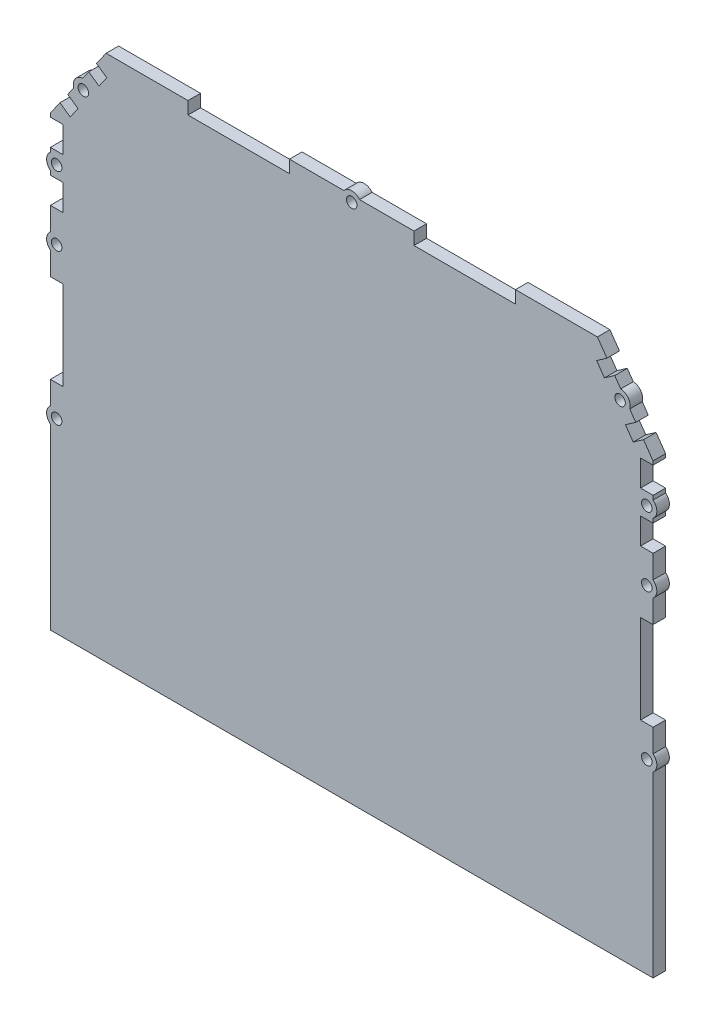
SolidWorks part; units mm, degrees
ref_plane "Front Plane" through (0, 0, 0) normal (0, 0, 1) x (1, 0, 0)
ref_plane "Top Plane" through (0, 0, 0) normal (0, 1, 0) x (1, 0, 0)
ref_plane "Right Plane" through (0, 0, 0) normal (1, 0, 0) x (0, 0, -1)
sketch "Sketch1" plane through (0, 0, 0) normal (0, 0, 1) x (1, 0, 0)
  line L0 (-120, 40) -> (-42.5, 40)
  line L1 (120, 105) -> (-120, 105)
  line L2 (120, 105) -> (120, 40)
  line L3 (120, -105) -> (-120, -105)
  line L4 (-120, 105) -> (-120, 40)
  line L5 (120, 105) -> (-120, -105) construction
  line L6 (120, -105) -> (-120, 105) construction
  line L7 (-42.5, 40) -> (-42.5, -40)
  line L8 (-42.5, -40) -> (-120, -40)
  line L9 (120, 40) -> (42.5, 40)
  line L10 (42.5, 40) -> (42.5, -40)
  line L11 (42.5, -40) -> (120, -40)
  line L12 (-120, -40) -> (-120, -105)
  line L13 (120, -40) -> (120, -105)
  point P0 (0, 0)
  point P12 (-120, 0)
  point P15 (120, 0)
  point P16 (-42.5, 0)
  point P18 (42.5, 0)
  dimension "D1" = 240
  dimension "D2" = 210
  dimension "D3" = 77.5
  dimension "D4" = 77.5
  dimension "D5" = 80
extrude "Boss-Extrude1" add sketch "Sketch1" along normal blind 5
sketch "Sketch2" plane through (0, 0, 5) normal (0, 0, 1) x (1, 0, 0)
  line L0 (-120, -105) -> (120, -105) construction
  line L1 (40, -55.718) -> (-40, -55.718)
  line L2 (-40, -55.718) -> (-80, -125)
  line L3 (-80, -125) -> (-40, -194.282)
  line L4 (-40, -194.282) -> (40, -194.282)
  line L5 (40, -194.282) -> (80, -125)
  line L6 (80, -125) -> (40, -55.718)
  circle A0 centre (0, -125) radius 69.282 construction
  dimension "D1" = 160
  dimension "D2" = 20
extrude "Cut-Extrude1" cut sketch "Sketch2" against normal blind 5
sketch "Sketch5" plane through (0, 0, 5) normal (0, 0, 1) x (1, 0, 0)
  line L0 (-97.5, 95) -> (-101, 90) construction
  line L1 (-97.8239, 105) -> (-120, 73.3199)
  line L2 (120, 105) -> (-120, 105) construction
  line L3 (-120, 105) -> (-120, 40) construction
  line L4 (-97.8239, 105) -> (-120, 105)
  line L5 (-120, 105) -> (-120, 73.3199)
  line L6 (0, 105) -> (0, 62.0384) construction
  line L7 (97.8239, 105) -> (120, 105)
  line L8 (97.8239, 105) -> (120, 73.3199)
  line L9 (120, 105) -> (120, 73.3199)
  dimension "D1" = 6
extrude "Cut-Extrude4" cut sketch "Sketch5" against normal blind 5
sketch "Sketch7" plane through (0, 0, 0) normal (0, 0, -1) x (-1, 0, 0)
  line L0 (120, -40) -> (120, -105)
  line L1 (120, -40) -> (120, -105) construction
  line L2 (120, -105) -> (89.53, -105)
  line L5 (129.53, -122.5) -> (129.53, -40)
  line L6 (129.53, -40) -> (89.53, -40)
  line L7 (89.53, -40) -> (89.53, -64)
  line L8 (89.53, -105) -> (111.53, -122.5)
  line L9 (111.53, -122.5) -> (129.53, -122.5)
  line L10 (129.53, -122.5) -> (129.53, -40)
  line L11 (129.53, -40) -> (120, -40)
  line L13 (89.53, -105) -> (111.53, -122.5)
  line L14 (111.53, -122.5) -> (129.53, -122.5)
  line L40 (89.53, -94) -> (89.53, -105)
  arc A2 (89.53, -94) -> (89.53, -64) centre (89.53, -79) ccw
  dimension "D1" = 0
extrude "Boss-Extrude3" add sketch "Sketch7" against normal blind 5
mirror "Mirror2" about plane through (0, 0, 0) normal (1, 0, 0) of "Boss-Extrude3"
sketch "Sketch8" plane through (0, 0, 5) normal (0, 0, 1) x (1, 0, 0)
  line L0 (-108.912, 89.16) -> (-95.8237, 79.9982) construction
  line L1 (-113.2129, 83.0157) -> (-116.0802, 78.9196)
  line L14 (-120, 73.3199) -> (-97.8239, 105) construction
  line L15 (-100.5148, 92.4369) -> (-104.611, 95.3042)
  line L28 (-120, 56.66) -> (-98.9329, 56.66) construction
  line L29 (-120, 73.3199) -> (-120, 40) construction
  line L30 (0, 105) -> (0, 80.5082) construction
  line L31 (97.8239, 105) -> (-97.8239, 105) construction
  line L32 (-116.0802, 78.9196) -> (-111.9841, 76.0522)
  line L33 (-111.9841, 76.0522) -> (-109.1168, 80.1484)
  line L34 (-109.1168, 80.1484) -> (-113.2129, 83.0157)
  line L35 (-110.5504, 78.1003) -> (-114.6466, 80.9676) construction
  line L36 (-97.6475, 96.533) -> (-100.5148, 92.4369)
  line L37 (-101.7437, 99.4004) -> (-97.6475, 96.533)
  line L38 (-104.611, 95.3042) -> (-101.7437, 99.4004)
  line L39 (-120, 41.66) -> (-115, 41.66)
  line L40 (-115, 41.66) -> (-115, 51.66)
  line L41 (-115, 51.66) -> (-120, 51.66)
  line L42 (-120, 51.66) -> (-120, 41.66)
  line L43 (-115, 61.66) -> (-120, 61.66)
  line L44 (-115, 71.66) -> (-115, 61.66)
  line L45 (-120, 71.66) -> (-115, 71.66)
  line L46 (-120, 61.66) -> (-120, 71.66)
  line L47 (110.5504, 78.1003) -> (114.6466, 80.9676) construction
  line L48 (-65, 105) -> (-25, 105)
  line L49 (-65, 105) -> (-65, 100)
  line L50 (-65, 100) -> (-25, 100)
  line L51 (-25, 105) -> (-25, 100)
  line L52 (120, 56.66) -> (98.9329, 56.66) construction
  line L53 (108.912, 89.16) -> (95.8237, 79.9982) construction
  line L54 (25, 105) -> (25, 100)
  line L55 (65, 100) -> (25, 100)
  line L56 (65, 105) -> (65, 100)
  line L57 (65, 105) -> (25, 105)
  line L58 (120, 61.66) -> (120, 71.66)
  line L59 (120, 71.66) -> (115, 71.66)
  line L60 (115, 71.66) -> (115, 61.66)
  line L61 (115, 61.66) -> (120, 61.66)
  line L62 (120, 51.66) -> (120, 41.66)
  line L63 (115, 51.66) -> (120, 51.66)
  line L64 (115, 41.66) -> (115, 51.66)
  line L65 (120, 41.66) -> (115, 41.66)
  line L66 (104.611, 95.3042) -> (101.7437, 99.4004)
  line L67 (101.7437, 99.4004) -> (97.6475, 96.533)
  line L68 (97.6475, 96.533) -> (100.5148, 92.4369)
  line L69 (109.1168, 80.1484) -> (113.2129, 83.0157)
  line L70 (111.9841, 76.0522) -> (109.1168, 80.1484)
  line L71 (116.0802, 78.9196) -> (111.9841, 76.0522)
  line L72 (100.5148, 92.4369) -> (104.611, 95.3042)
  line L73 (113.2129, 83.0157) -> (116.0802, 78.9196)
  line L75 (97.8239, 105) -> (120, 73.3199) construction
  line L76 (120, 40) -> (120, 73.3199) construction
  circle A0 centre (0, 102.5) radius 2.1
  circle A2 centre (106.8639, 87.7263) radius 2.1
  circle A3 centre (117.5, 56.66) radius 2.1
  circle A4 centre (-117.5, 56.66) radius 2.1
  circle A5 centre (-106.8639, 87.7263) radius 2.1
  dimension "D10" = 4.2
  dimension "D11" = 2.5
  dimension "D12" = 4.2
  dimension "D13" = 2.5
  dimension "D14" = 4.2
  dimension "D15" = 2.5
  dimension "D3" = 10
  dimension "D1" = 5
  dimension "D2" = 5
  dimension "D4" = 10
  dimension "D5" = 5
  dimension "D6" = 5
  dimension "D7" = 40
  dimension "D8" = 5
  dimension "D9" = 25
extrude "Cut-Extrude5" cut sketch "Sketch8" against normal blind 10
sketch "Sketch9" plane through (0, 0, 5) normal (0, 0, 1) x (1, 0, 0)
  line L0 (-3.1225, 105) -> (3.1225, 105)
  line L1 (25, 105) -> (-25, 105) construction
  line L2 (107.1213, 91.718) -> (110.7026, 86.6019)
  line L3 (104.611, 95.3042) -> (113.2129, 83.0157) construction
  line L4 (120, 59.7825) -> (120, 53.5375)
  line L5 (120, 51.66) -> (120, 61.66) construction
  line L6 (0, 102.5) -> (0, 84.4431) construction
  line L7 (-120, 59.7825) -> (-120, 53.5375)
  line L8 (-107.1213, 91.718) -> (-110.7026, 86.6019)
  arc A0 (3.1225, 105) -> (-3.1225, 105) centre (0, 102.5) ccw
  arc A1 (110.7026, 86.6019) -> (107.1213, 91.718) centre (106.8639, 87.7263) ccw
  arc A2 (120, 53.5375) -> (120, 59.7825) centre (117.5, 56.66) ccw
  arc A3 (-120, 53.5375) -> (-120, 59.7825) centre (-117.5, 56.66) cw
  arc A4 (-110.7026, 86.6019) -> (-107.1213, 91.718) centre (-106.8639, 87.7263) cw
  dimension "D1" = 8
  dimension "D2" = 8
  dimension "D3" = 8
extrude "Boss-Extrude4" add sketch "Sketch9" against normal blind 5
sketch "Sketch10" plane through (0, 0, 5) normal (0, 0, 1) x (1, 0, 0)
  line L0 (-120, 40) -> (-120, -40)
  line L1 (-68.453, -105) -> (68.453, -105)
  line L2 (120, -40) -> (120, 40)
  line L3 (68.453, -105) -> (89.53, -105) construction
  line L4 (-120, 40) -> (-42.5, 40)
  line L5 (-42.5, 40) -> (-42.5, -40)
  line L6 (-42.5, -40) -> (-120, -40)
  line L7 (-42.5, -40) -> (-129.53, -40) construction
  line L8 (-40, -55.718) -> (-68.453, -105)
  line L9 (-40, -55.718) -> (40, -55.718)
  line L10 (40, -55.718) -> (68.453, -105)
  line L11 (120, -40) -> (42.5, -40)
  line L12 (129.53, -40) -> (42.5, -40) construction
  line L13 (42.5, -40) -> (42.5, 40)
  line L14 (42.5, 40) -> (120, 40)
  point P9 (78.9915, -105)
extrude "Boss-Extrude5" add sketch "Sketch10" against normal blind 5
sketch "Sketch11" plane through (0, 0, 5) normal (0, 0, 1) x (1, 0, 0)
  line L0 (-120, -40) -> (-120, -105)
  line L1 (-120, -105) -> (120, -105)
  line L2 (120, -105) -> (120, -40)
  line L3 (120, -40) -> (129.53, -40)
  line L4 (129.53, -40) -> (129.53, -122.5)
  line L5 (129.53, -122.5) -> (-129.53, -122.5)
  line L6 (-129.53, -122.5) -> (-129.53, -40)
  line L7 (-129.53, -40) -> (-120, -40)
  line L8 (-89.53, -105) -> (89.53, -105) construction
extrude "Cut-Extrude6" cut sketch "Sketch11" against normal blind 5
sketch "Sketch12" plane through (0, 0, 5) normal (0, 0, 1) x (1, 0, 0)
  line L0 (-120, 41.66) -> (-120, -105) construction
  line L1 (-120, 16.66) -> (-115, 16.66)
  line L2 (-120, 16.66) -> (-120, -18.34)
  line L3 (-120, -18.34) -> (-115, -18.34)
  line L4 (-115, 16.66) -> (-115, -18.34)
  line L5 (-120, 41.66) -> (-115, 41.66) construction
  line L6 (0, 0) -> (0, -46.7623) construction
  line L7 (115, 16.66) -> (115, -18.34)
  line L8 (120, -18.34) -> (115, -18.34)
  line L9 (120, 16.66) -> (120, -18.34)
  line L10 (120, 16.66) -> (115, 16.66)
  circle A0 centre (-117.5, 29.16) radius 2.1
  circle A1 centre (-117.5, -30.84) radius 2.1
  circle A2 centre (117.5, -30.84) radius 2.1
  circle A3 centre (117.5, 29.16) radius 2.1
  dimension "D3" = 4.2
  dimension "D4" = 2.5
  dimension "D5" = 12.5
  dimension "D7" = 4.2
  dimension "D8" = 12.5
  dimension "D9" = 2.5
  dimension "D1" = 35
  dimension "D2" = 25
  dimension "D6" = 5
extrude "Cut-Extrude7" cut sketch "Sketch12" against normal blind 5
sketch "Sketch13" plane through (0, 0, 5) normal (0, 0, 1) x (1, 0, 0)
  line L0 (-120, 32.2825) -> (-120, 26.0375)
  line L1 (-120, 41.66) -> (-120, 16.66) construction
  line L2 (-120, -27.7175) -> (-120, -33.9625)
  line L3 (-120, -18.34) -> (-120, -105) construction
  line L4 (0, 0) -> (0, -42.8158) construction
  line L5 (120, -27.7175) -> (120, -33.9625)
  line L6 (120, 32.2825) -> (120, 26.0375)
  arc A0 (-120, 32.2825) -> (-120, 26.0375) centre (-117.5, 29.16) ccw
  arc A1 (-120, -27.7175) -> (-120, -33.9625) centre (-117.5, -30.84) ccw
  arc A2 (120, -27.7175) -> (120, -33.9625) centre (117.5, -30.84) cw
  arc A3 (120, 32.2825) -> (120, 26.0375) centre (117.5, 29.16) cw
  dimension "D1" = 8
  dimension "D2" = 8
extrude "Boss-Extrude6" add sketch "Sketch13" against normal blind 5
sketch "Sketch14" plane through (0, 0, 5) normal (0, 0, 1) x (1, 0, 0)
  line L0 (-104.7257, 95.1403) -> (-100.6295, 92.273)
  line L1 (-107.1213, 91.718) -> (-104.611, 95.3042) construction
  line L2 (-100.6295, 92.273) -> (-97.5328, 96.6969)
  line L3 (-97.5328, 96.6969) -> (-101.629, 99.5642)
  line L4 (-101.7437, 99.4004) -> (-97.8239, 105) construction
  line L5 (-104.611, 95.3042) -> (-100.5148, 92.4369) construction
  line L6 (-100.5148, 92.4369) -> (-97.6475, 96.533) construction
  line L7 (-110.1408, 90.0201) -> (-106.8639, 87.7263) construction
  line L8 (-112.0988, 75.8884) -> (-116.1949, 78.7557)
  line L9 (-109.0021, 80.3122) -> (-112.0988, 75.8884)
  line L10 (-113.0982, 83.1796) -> (-109.0021, 80.3122)
  line L11 (-120, 73.3199) -> (-120, 71.66) construction
  line L12 (-120, 71.86) -> (-115, 71.86)
  line L13 (-120, 71.86) -> (-120, 61.46)
  line L14 (-120, 61.46) -> (-115, 61.46)
  line L15 (-115, 71.86) -> (-115, 61.46)
  line L16 (-120, 61.66) -> (-115, 61.66) construction
  line L17 (-121.5, 56.66) -> (-117.5, 56.66) construction
  line L18 (-115, 41.46) -> (-115, 51.86)
  line L19 (-120, 51.86) -> (-115, 51.86)
  line L20 (-120, 41.46) -> (-120, 51.86)
  line L21 (-120, 41.46) -> (-115, 41.46)
  line L22 (-120, -18.34) -> (-120, -27.7175) construction
  line L23 (-115, 16.86) -> (-120, 16.86)
  line L24 (-115, 16.86) -> (-115, -18.54)
  line L25 (-115, -18.54) -> (-120, -18.54)
  line L26 (-120, 16.86) -> (-120, -18.54)
  line L27 (-120, -18.34) -> (-115, -18.34) construction
  line L28 (-65, 105) -> (-97.8239, 105) construction
  line L29 (-65.2, 105) -> (-24.8, 105)
  line L30 (-65.2, 105) -> (-65.2, 100)
  line L31 (-65.2, 100) -> (-24.8, 100)
  line L32 (-24.8, 105) -> (-24.8, 100)
  line L33 (-65, 105) -> (-65, 100) construction
  line L34 (0, 102.5) -> (0, 85.714) construction
  line L35 (24.8, 105) -> (24.8, 100)
  line L36 (65.2, 100) -> (24.8, 100)
  line L37 (65.2, 105) -> (65.2, 100)
  line L38 (65.2, 105) -> (24.8, 105)
  line L39 (121.5, 56.66) -> (117.5, 56.66) construction
  line L40 (110.1408, 90.0201) -> (106.8639, 87.7263) construction
  line L41 (120, 16.86) -> (120, -18.54)
  line L42 (115, -18.54) -> (120, -18.54)
  line L43 (115, 16.86) -> (115, -18.54)
  line L44 (115, 16.86) -> (120, 16.86)
  line L45 (120, 41.46) -> (115, 41.46)
  line L46 (120, 41.46) -> (120, 51.86)
  line L47 (120, 51.86) -> (115, 51.86)
  line L48 (115, 41.46) -> (115, 51.86)
  line L49 (115, 71.86) -> (115, 61.46)
  line L50 (120, 61.46) -> (115, 61.46)
  line L51 (120, 71.86) -> (120, 61.46)
  line L52 (120, 71.86) -> (115, 71.86)
  line L53 (113.0982, 83.1796) -> (109.0021, 80.3122)
  line L54 (109.0021, 80.3122) -> (112.0988, 75.8884)
  line L55 (112.0988, 75.8884) -> (116.1949, 78.7557)
  line L56 (97.5328, 96.6969) -> (101.629, 99.5642)
  line L57 (100.6295, 92.273) -> (97.5328, 96.6969)
  line L58 (104.7257, 95.1403) -> (100.6295, 92.273)
  line L59 (-101.629, 99.5642) -> (-104.7257, 95.1403)
  line L60 (-113.0982, 83.1796) -> (-116.1949, 78.7557)
  line L61 (101.629, 99.5642) -> (104.7257, 95.1403)
  line L62 (113.0982, 83.1796) -> (116.1949, 78.7557)
  arc A0 (-107.1213, 91.718) -> (-110.7026, 86.6019) centre (-106.8639, 87.7263) ccw construction
  arc A1 (-120, 59.7825) -> (-120, 53.5375) centre (-117.5, 56.66) ccw construction
  dimension "D1" = 5.4
  dimension "D2" = 0.2
  dimension "D3" = 5
  dimension "D4" = 10.4
  dimension "D5" = 0.2
  dimension "D6" = 5
  dimension "D7" = 35.4
  dimension "D8" = 0.2
  dimension "D9" = 5
  dimension "D10" = 0.2
  dimension "D11" = 40.4
extrude "Cut-Extrude8" cut sketch "Sketch14" against normal blind 10
